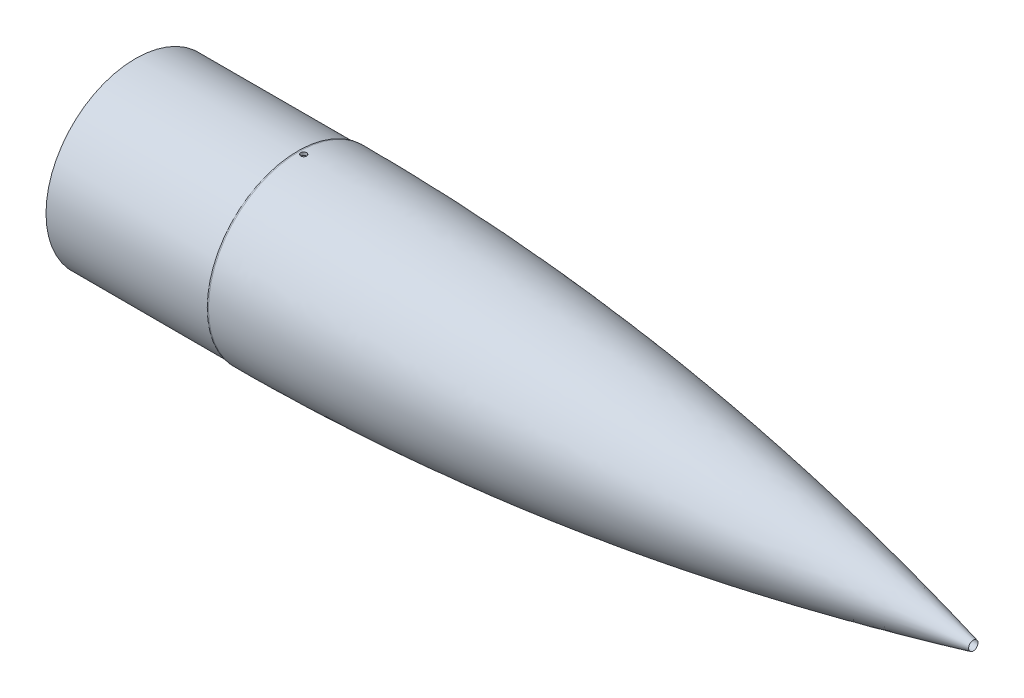
SolidWorks part; units mm, degrees
material "ABS"
ref_plane "Plan de face" through (0, 0, 0) normal (0, 0, 1) x (1, 0, 0)
ref_plane "Plan de dessus" through (0, 0, 0) normal (0, 1, 0) x (1, 0, 0)
ref_plane "Plan de droite" through (0, 0, 0) normal (1, 0, 0) x (0, 0, -1)
sketch "Esquisse1" plane through (0, 0, 0) normal (0, 0, 1) x (1, 0, 0)
  line L0 (-218.2881, 0) -> (241.2348, 0) construction
  line L1 (-491.5041, 74.5) -> (-490.5041, 74.5)
  line L2 (-490.5041, 74.5) -> (-210.6412, 74.5) construction
  line L3 (-210.6412, 74.5) -> (88.162, 0) construction
  line L4 (-491.5041, 77) -> (-490.5041, 77)
  line L5 (-491.5041, 74.5) -> (-491.5041, 77)
  line L6 (88.7668, 2.4257) -> (98.4959, 0)
  line L7 (98.4959, 0) -> (88.162, 0)
  spline S0 degree 1 poles (-490.5041, 77) (88.7668, 2.4257) knots 0 0 1 1 construction
  spline S1 degree 2 poles (-490.5041, 74.5) (-210.6412, 74.5) (88.162, 0) knots 0 0 0 1 1 1
  spline S2 degree 3 poles (-490.5041, 77) (-484.6605, 77) (-472.9823, 76.9514) (-449.5545, 76.6601) (-420.1851, 75.9317) (-384.791, 74.4749) (-337.4033, 71.7557) (-277.7995, 66.9001) (-205.6852, 58.7429) (-132.981, 48.2555) (-71.9032, 37.5744) (-22.7455, 27.8644) (14.2685, 19.9999) (45.2414, 12.9596) (70.0821, 7.0389) (82.5476, 3.9764) (88.7668, 2.4257) knots 0 0 0 0 0.03125 0.0625 0.125 0.1875 0.25 0.375 0.5 0.625 0.75 0.8125 0.875 0.9375 0.96875 1 1 1 1
  dimension "D1" = 77
  dimension "D2" = 14
  dimension "D3" = 1
  dimension "D5" = 2.5
  dimension "D7" = 590
revolve "Révolution3" add sketch "Esquisse1" angle 360 about L0
sketch "Esquisse2" plane through (-491.5041, 0, 0) normal (-1, 0, 0) x (0, 0, 1)
  circle A0 centre (0, 0) radius 76
  circle A1 centre (0, 0) radius 74.5
  dimension "D1" = 149
  dimension "D2" = 152
extrude "Boss.-Extru.1" add sketch "Esquisse2" along normal blind 138
sketch "Esquisse3" plane through (0, 0, 0) normal (0, 1, 0) x (1, 0, 0)
  line L1 (-491.5041, 77) -> (-491.5041, -77) construction
  circle A0 centre (-486.5041, 0) radius 2.5
  dimension "D1" = 5
  dimension "D2" = 5
extrude "Enlèv. mat.-Extru.1" cut sketch "Esquisse3" against normal through all both and the other way through all contours A0
sketch "Esquisse4" plane through (0, 0, 0) normal (1, 0, 0) x (0, 0, -1)
  circle A0 centre (0, 0) radius 4
  dimension "D1" = 8
extrude "Enlèv. mat.-Extru.2" cut sketch "Esquisse4" along normal through all
